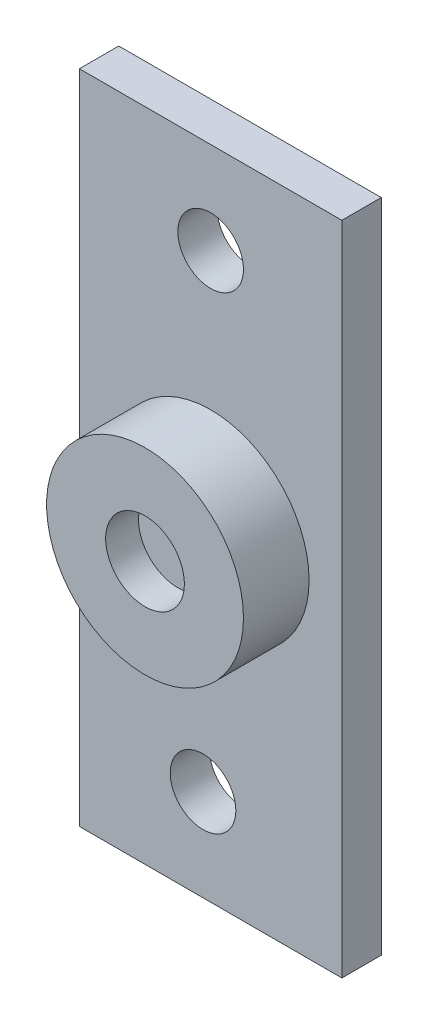
SolidWorks part; units mm, degrees
ref_plane "前视基准面" through (0, 0, 0) normal (0, 0, 1) x (1, 0, 0)
ref_plane "上视基准面" through (0, 0, 0) normal (0, 1, 0) x (1, 0, 0)
ref_plane "右视基准面" through (0, 0, 0) normal (1, 0, 0) x (0, 0, -1)
sketch "草图1" plane through (0, 0, 0) normal (0, 0, 1) x (1, 0, 0)
  line L1 (10, -25) -> (-10, -25)
  line L2 (10, -25) -> (10, 25)
  line L3 (10, 25) -> (-10, 25)
  line L4 (-10, -25) -> (-10, 25)
  line L5 (10, -25) -> (-10, 25) construction
  line L6 (10, 25) -> (-10, -25) construction
  point P0 (0, 0)
  dimension "D1" = 20
  dimension "D2" = 50
extrude "凸台-拉伸1" add sketch "草图1" along normal blind 3
sketch "草图2" plane through (0, 0, 3) normal (0, 0, 1) x (1, 0, 0)
  circle A0 centre (0, 0) radius 7.5
  dimension "D1" = 15
extrude "凸台-拉伸2" add sketch "草图2" along normal blind 5
sketch "草图3" plane through (0, 0, 8) normal (0, 0, 1) x (1, 0, 0)
  circle A0 centre (0, 0) radius 3
  dimension "D1" = 6
extrude "切除-拉伸1" cut sketch "草图3" against normal blind 2.5
sketch "草图4" plane through (0, 0, 3) normal (0, 0, 1) x (1, 0, 0)
  circle A0 centre (0, 18) radius 2.5
  circle A1 centre (-0.5807, -18) radius 2.5
  dimension "D1" = 5
  dimension "D2" = 5
  dimension "D3" = 18
  dimension "D4" = 18
extrude "切除-拉伸2" cut sketch "草图4" against normal blind 3
